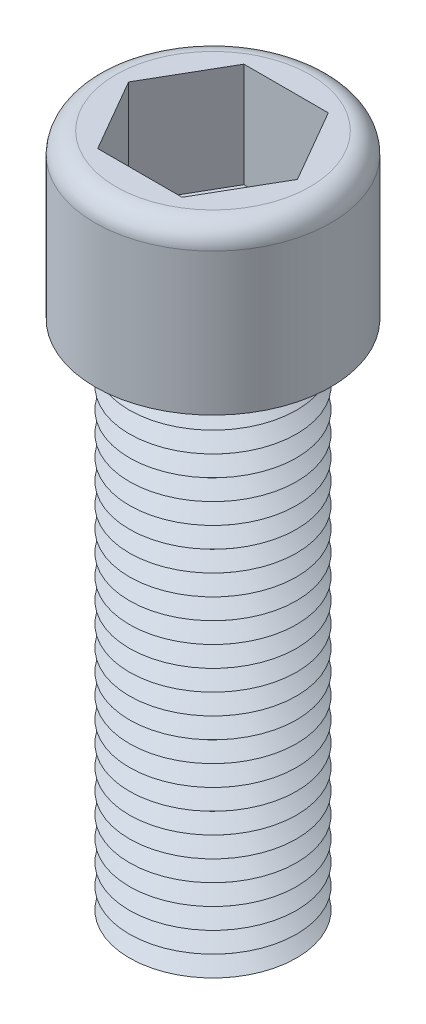
SolidWorks part; units mm, degrees
ref_plane "前视基准面" through (0, 0, 0) normal (0, 0, 1) x (1, 0, 0)
ref_plane "上视基准面" through (0, 0, 0) normal (0, 1, 0) x (1, 0, 0)
ref_plane "右视基准面" through (0, 0, 0) normal (1, 0, 0) x (0, 0, -1)
sketch "草图4" plane through (0, 0, 0) normal (0, 0, 1) x (1, 0, 0)
  line B0 (0, 0) -> (0, 32.8)
  line B1 (5.65, 25) -> (5.65, 31.8)
  line B2 (4.65, 32.8) -> (0, 32.8)
  line B3 (5.65, 25) -> (3.7384, 25)
  line B4 (3.3, 0) -> (4, 0.4938)
  line B5 (3.3, 0) -> (0, 0)
  line B6 (3.3, 0.9876) -> (4, 0.4938)
  line B7 (3.3, 0.9876) -> (4, 1.4814)
  line B8 (3.3, 1.9753) -> (4, 1.4814)
  line B9 (3.3, 1.9753) -> (4, 2.4691)
  line B10 (3.3, 2.9629) -> (4, 2.4691)
  line B11 (3.3, 2.9629) -> (4, 3.4567)
  line B12 (3.3, 3.9505) -> (4, 3.4567)
  line B13 (3.3, 3.9505) -> (4, 4.4443)
  line B14 (3.3, 4.9381) -> (4, 4.4443)
  line B15 (3.3, 4.9381) -> (4, 5.432)
  line B16 (3.3, 5.9258) -> (4, 5.432)
  line B17 (3.3, 5.9258) -> (4, 6.4196)
  line B18 (3.3, 6.9134) -> (4, 6.4196)
  line B19 (3.3, 6.9134) -> (4, 7.4072)
  line B20 (3.3, 7.901) -> (4, 7.4072)
  line B21 (3.3, 7.901) -> (4, 8.3949)
  line B22 (3.3, 8.8887) -> (4, 8.3949)
  line B23 (3.3, 8.8887) -> (4, 9.3825)
  line B24 (3.3, 9.8763) -> (4, 9.3825)
  line B25 (3.3, 9.8763) -> (4, 10.3701)
  line B26 (3.3, 10.8639) -> (4, 10.3701)
  line B27 (3.3, 10.8639) -> (4, 11.3577)
  line B28 (3.3, 11.8516) -> (4, 11.3577)
  line B29 (3.3, 11.8516) -> (4, 12.3454)
  line B30 (3.3, 12.8392) -> (4, 12.3454)
  line B31 (3.3, 12.8392) -> (4, 13.333)
  line B32 (3.3, 13.8268) -> (4, 13.333)
  line B33 (3.3, 13.8268) -> (4, 14.3206)
  line B34 (3.3, 14.8144) -> (4, 14.3206)
  line B35 (3.3, 14.8144) -> (4, 15.3083)
  line B36 (3.3, 15.8021) -> (4, 15.3083)
  line B37 (3.3, 15.8021) -> (4, 16.2959)
  line B38 (3.3, 16.7897) -> (4, 16.2959)
  line B39 (3.3, 16.7897) -> (4, 17.2835)
  line B40 (3.3, 17.7773) -> (4, 17.2835)
  line B41 (3.3, 17.7773) -> (4, 18.2712)
  line B42 (3.3, 18.765) -> (4, 18.2712)
  line B43 (3.3, 18.765) -> (4, 19.2588)
  line B44 (3.3, 19.7526) -> (4, 19.2588)
  line B45 (3.3, 19.7526) -> (4, 19.2588)
  line B46 (3.3, 19.7526) -> (4, 20.2464)
  line B47 (3.3, 20.7402) -> (4, 20.2464)
  line B48 (3.3, 20.7402) -> (4, 21.234)
  line B49 (3.3, 21.7279) -> (4, 21.234)
  line B50 (3.3, 21.7279) -> (4, 22.2217)
  line B51 (3.3, 22.7155) -> (4, 22.2217)
  line B52 (3.3, 22.7155) -> (4, 23.2093)
  line B53 (3.3, 23.7031) -> (4, 23.2093)
  line B54 (3.3, 23.7031) -> (4, 24.1969)
  line B55 (3.3, 24.6907) -> (4, 24.1969)
  line B56 (3.3, 24.6907) -> (3.7384, 25)
  arc B57 (5.65, 31.8) -> (4.65, 32.8) centre (4.65, 31.8) ccw
sketch_block_instance "A$C0C7D5D1D_0-1"
sketch_block "A$C0C7D5D1D_0"
revolve "旋转3" add sketch "草图4" angle 360 about L0
sketch "草图6" plane through (0, 32.8, 0) normal (0, 1, 0) x (1, 0, 0)
  line L1 (4.0415, 0) -> (2.0207, 3.5)
  line L2 (2.0207, 3.5) -> (-2.0207, 3.5)
  line L3 (-2.0207, 3.5) -> (-4.0415, 0)
  line L4 (-4.0415, 0) -> (-2.0207, -3.5)
  line L5 (-2.0207, -3.5) -> (2.0207, -3.5)
  line L6 (2.0207, -3.5) -> (4.0415, 0)
  circle A0 centre (0, 0) radius 3.5 construction
extrude "切除-拉伸1" cut sketch "草图6" against normal blind 5
